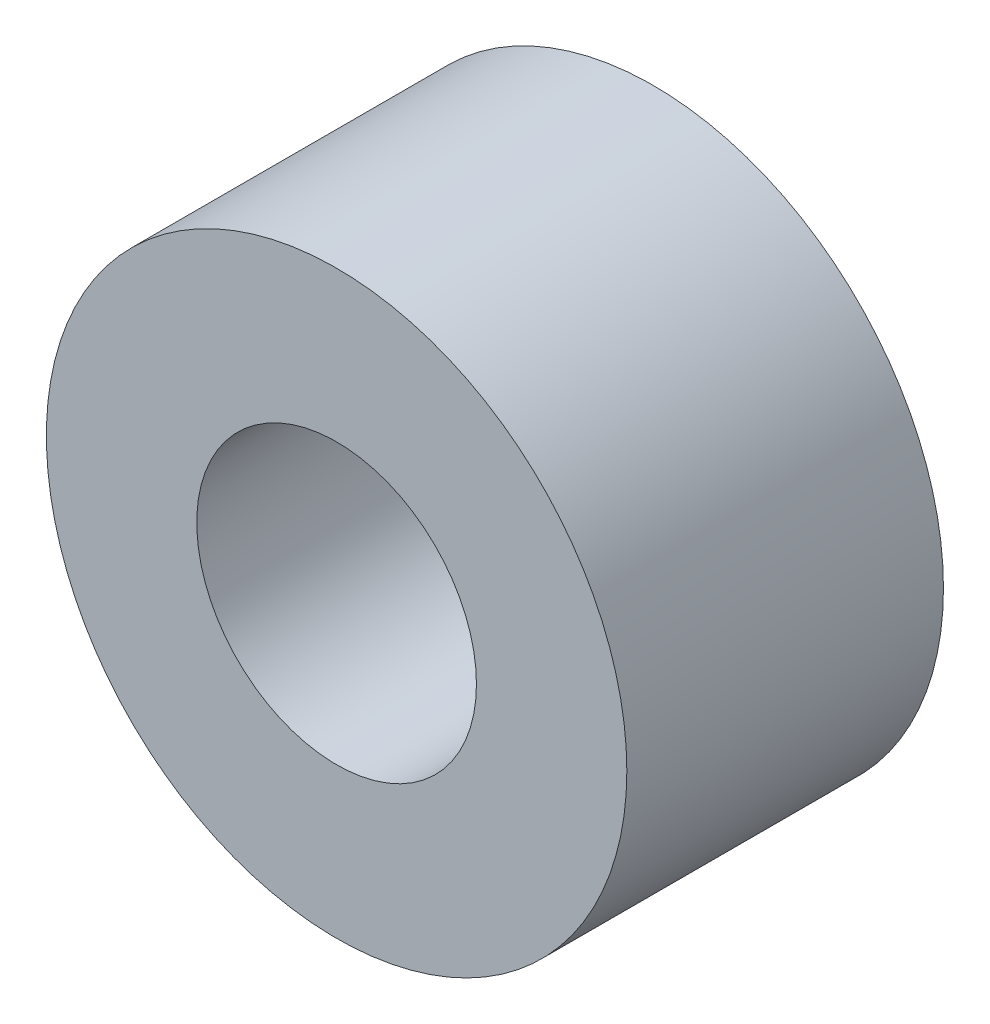
SolidWorks part; units mm, degrees
material "ABS"
ref_plane "Alzado" through (0, 0, 0) normal (0, 0, 1) x (1, 0, 0)
ref_plane "Planta" through (0, 0, 0) normal (0, 1, 0) x (1, 0, 0)
ref_plane "Vista lateral" through (0, 0, 0) normal (1, 0, 0) x (0, 0, -1)
sketch "Croquis1" plane through (0, 0, 0) normal (0, 0, 1) x (1, 0, 0)
  circle A0 centre (0, 0) radius 5.5
  circle A1 centre (0, 0) radius 2.65
  dimension "D1" = 11
  dimension "D2" = 5.3
extrude "Saliente-Extruir1" add sketch "Croquis1" along normal blind 6
